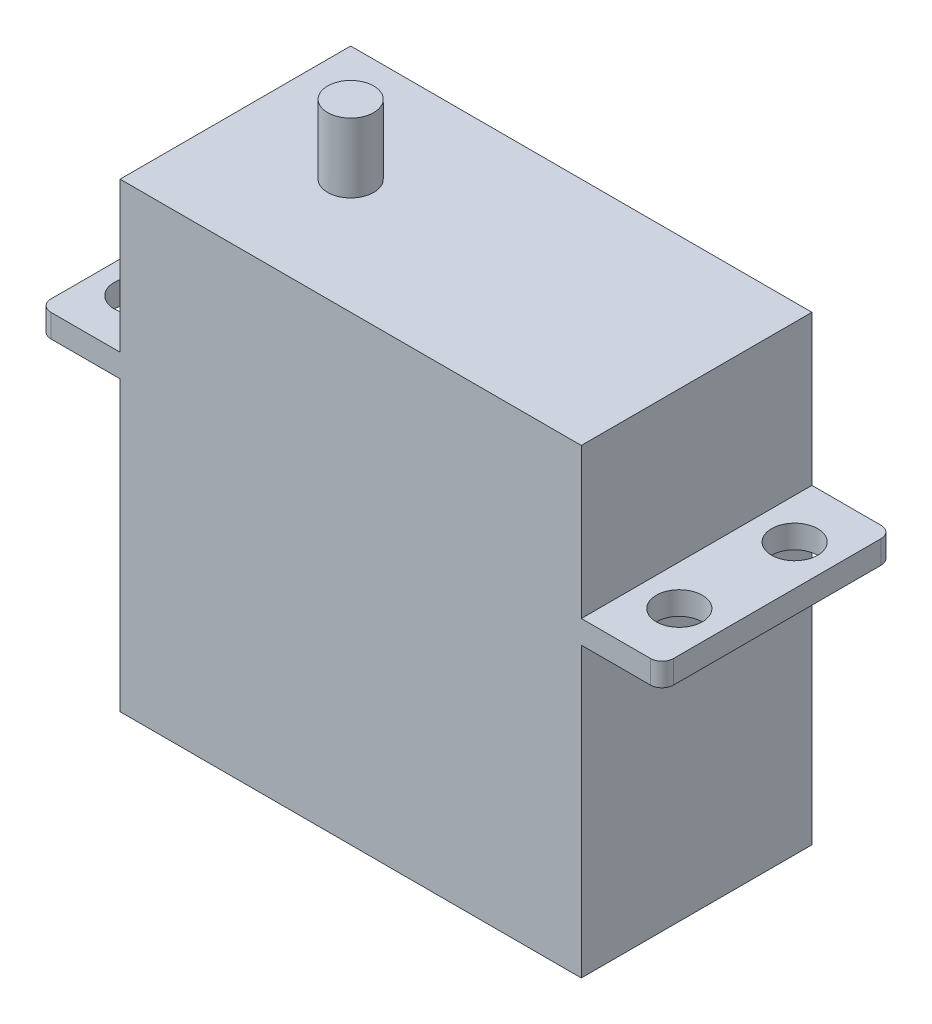
SolidWorks part; units mm, degrees
ref_plane "Ön Düzlem" through (0, 0, 0) normal (0, 0, 1) x (1, 0, 0)
ref_plane "Üst Düzlem" through (0, 0, 0) normal (0, 1, 0) x (1, 0, 0)
ref_plane "Sağ Düzlem" through (0, 0, 0) normal (1, 0, 0) x (0, 0, -1)
sketch "Çizim1" plane through (0, 0, 0) normal (0, 0, 1) x (1, 0, 0)
  line L1 (0, 0) -> (40, 0)
  line L2 (0, 0) -> (0, 25)
  line L3 (0, 40) -> (40, 40)
  line L4 (40, 0) -> (40, 25)
  line L5 (40, 25) -> (47, 25)
  line L7 (40, 27) -> (47, 27)
  line L8 (47, 25) -> (47, 27)
  line L9 (-7, 25) -> (-7, 27)
  line L10 (0, 27) -> (-7, 27)
  line L11 (0, 25) -> (-7, 25)
  line L12 (0, 27) -> (0, 40)
  line L13 (40, 27) -> (40, 40)
  dimension "D1" = 40
  dimension "D2" = 40
  dimension "D3" = 25
  dimension "D4" = 2
  dimension "D5" = 7
  dimension "D6" = 7
extrude "Yükseklik-Ekstrüzyon1" add sketch "Çizim1" along normal blind 20
fillet "Radyus1" radius 1 4 edges at (-7, 26, 0) (-7, 26, 20) (47, 26, 0) (47, 26, 20)
sketch "Çizim2" plane through (0, 27, 0) normal (0, 1, 0) x (1, 0, 0)
  line L0 (-7, -10) -> (0, -10)
  line L1 (-7, -19) -> (-7, -1) construction
  line L2 (0, -20) -> (0, 0) construction
  line L7 (20, -20) -> (20, 0) construction
  line L8 (40, -20) -> (0, -20) construction
  line L9 (40, 0) -> (0, 0) construction
  circle A0 centre (-3.5, -5) radius 2
  circle A1 centre (-3.5, -15) radius 2
  circle A2 centre (43.5, -15) radius 2
  circle A3 centre (43.5, -5) radius 2
  dimension "D1" = 4
extrude "Kes-Ekstrüzyon1" cut sketch "Çizim2" against normal up to next contours A0 | A1 | A3 | A2
sketch "Çizim3" plane through (0, 40, 0) normal (0, 1, 0) x (1, 0, 0)
  line L0 (0, -20) -> (0, 0) construction
  line L1 (40, 0) -> (0, 0) construction
  circle A0 centre (10, -10) radius 2
  dimension "D1" = 4
  dimension "D2" = 10
  dimension "D3" = 10
extrude "Yükseklik-Ekstrüzyon2" add sketch "Çizim3" along normal blind 6
